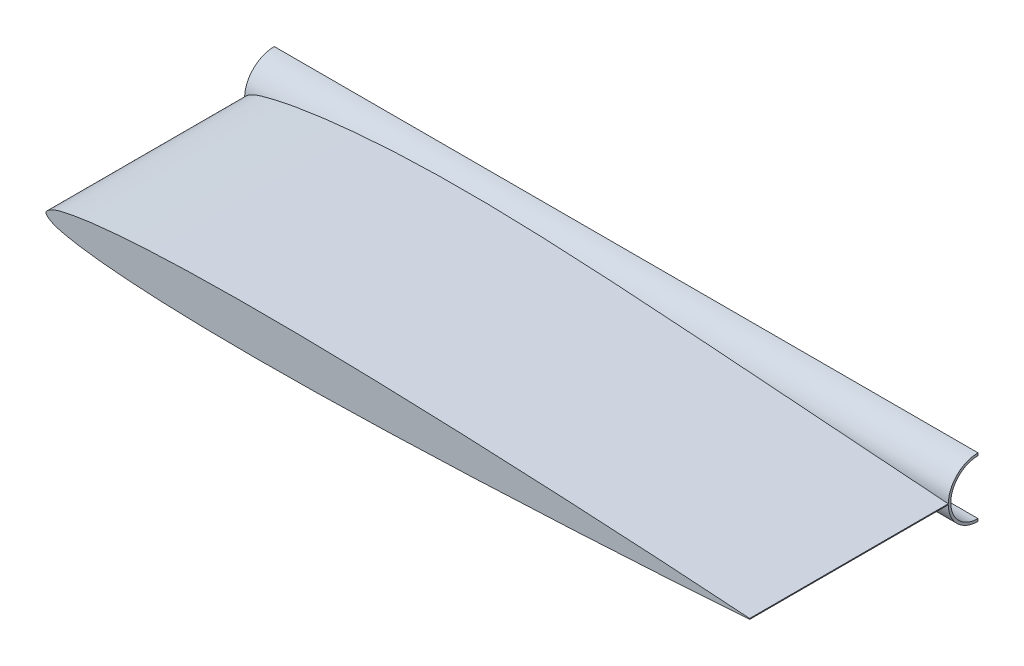
SolidWorks part; units mm, degrees
ref_plane "Front Plane" through (0, 0, 0) normal (0, 0, 1) x (1, 0, 0)
ref_plane "Top Plane" through (0, 0, 0) normal (0, 1, 0) x (1, 0, 0)
ref_plane "Right Plane" through (0, 0, 0) normal (1, 0, 0) x (0, 0, -1)
curve "Curve1"
  spline degree 3 poles (25.4, 0.016, 0) (24.9767, 0.0451, 0) (24.1302, 0.1034, 0) (22.437, 0.2117, 0) (20.3205, 0.3361, 0) (17.7804, 0.4681, 0) (15.2404, 0.5832, 0) (12.7004, 0.6768, 0) (10.1604, 0.7436, 0) (8.0434, 0.7669, 0) (6.3499, 0.7577, 0) (5.0797, 0.7326, 0) (3.8089, 0.6843, 0) (2.7512, 0.6171, 0) (1.9027, 0.5359, 0) (1.272, 0.4592, 0) (0.7223, 0.3537, 0) (0.3193, 0.2604, 0) (-0.1745, 0, 0) (0.3193, -0.2604, 0) (0.7223, -0.3537, 0) (1.272, -0.4592, 0) (1.9027, -0.5359, 0) (2.7512, -0.6171, 0) (3.8089, -0.6843, 0) (5.0797, -0.7326, 0) (6.3499, -0.7577, 0) (8.0434, -0.7669, 0) (10.1604, -0.7436, 0) (12.7004, -0.6768, 0) (15.2404, -0.5832, 0) (17.7804, -0.4681, 0) (20.3205, -0.3361, 0) (22.437, -0.2117, 0) (24.1302, -0.1034, 0) (24.9767, -0.0451, 0) (25.4, -0.016, 0) knots 0 0 0 0 0.024925 0.049843 0.099663 0.149465 0.199249 0.249016 0.298767 0.348504 0.373371 0.398243 0.42313 0.448052 0.460543 0.47308 0.485731 0.492201 0.5 0.507799 0.514269 0.52692 0.539457 0.551948 0.57687 0.601757 0.626629 0.651496 0.701233 0.750984 0.800751 0.850535 0.900337 0.950157 0.975075 1 1 1 1
sketch "Sketch1" plane through (0, 0, 0) normal (0, 0, 1) x (1, 0, 0)
  line L0 (571.5, 0.36) -> (571.5, -0.36)
  line L1 (571.5, 0) -> (0, 0) construction
  line L2 (0, 0) -> (0, 17.1507) construction
  line L3 (0, 17.1507) -> (171.3481, 17.1507) construction
  line L4 (0, 0) -> (0, -17.1507) construction
  line L5 (0, -17.1507) -> (171.3481, -17.1507) construction
  spline S1 degree 3 poles (571.5, 0.36) (561.9755, 1.0154) (542.9289, 2.3259) (504.8322, 4.763) (457.2107, 7.5622) (400.0596, 10.5332) (342.9099, 13.1215) (285.7598, 15.228) (228.6083, 16.7302) (180.9761, 17.2549) (142.8721, 17.0473) (114.2937, 16.4832) (85.7004, 15.3962) (61.9024, 13.8854) (42.8099, 12.0569) (28.6197, 10.3328) (16.2516, 7.9584) (7.1849, 5.8581) (-3.9273, 0) (7.1849, -5.8581) (16.2516, -7.9584) (28.6197, -10.3328) (42.8099, -12.0569) (61.9024, -13.8854) (85.7004, -15.3962) (114.2937, -16.4832) (142.8721, -17.0473) (180.9761, -17.2549) (228.6083, -16.7302) (285.7598, -15.228) (342.9099, -13.1215) (400.0596, -10.5332) (457.2107, -7.5622) (504.8322, -4.763) (542.9289, -2.3259) (561.9755, -1.0154) (571.5, -0.36) knots 0 0 0 0 0.024925 0.049843 0.099663 0.149465 0.199249 0.249016 0.298767 0.348504 0.373371 0.398243 0.42313 0.448052 0.460543 0.47308 0.485731 0.492201 0.5 0.507799 0.514269 0.52692 0.539457 0.551948 0.57687 0.601757 0.626629 0.651496 0.701233 0.750984 0.800751 0.850535 0.900337 0.950157 0.975075 1 1 1 1
  dimension "D1" = 571.5
extrude "Boss-Extrude1" add sketch "Sketch1" along normal blind 185.42
sketch "Sketch2" plane through (571.5, 0, 0) normal (1, 0, 0) x (0, 0, -1)
  line L0 (0, -24.13) -> (0, 24.13)
  arc A0 (0, -24.13) -> (0, 24.13) centre (0, 0) cw
  point P7 (0, 0)
  dimension "D1" = 24.13
extrude "Boss-Extrude2" add sketch "Sketch2" against normal up to vertex (571.5 mm away) up to point (0, 0, 0)
sketch "Sketch3" plane through (0, 0, 0) normal (-1, 0, 0) x (0, 0, 1)
  line L0 (0, -24.13) -> (0, 24.13) construction
  line L1 (0, 22.098) -> (0, -22.098)
  arc A0 (0, 22.098) -> (0, -22.098) centre (0, 0) cw
  dimension "D1" = 22.098
extrude "Cut-Extrude1" cut sketch "Sketch3" against normal through all both and the other way through all
sketch "Sketch4" plane through (0, 0, 185.42) normal (0, 0, 1) x (1, 0, 0)
  line L0 (571.5, 0) -> (0, 0) construction
  line L1 (571.5, -0.36) -> (571.5, 0.36) construction
